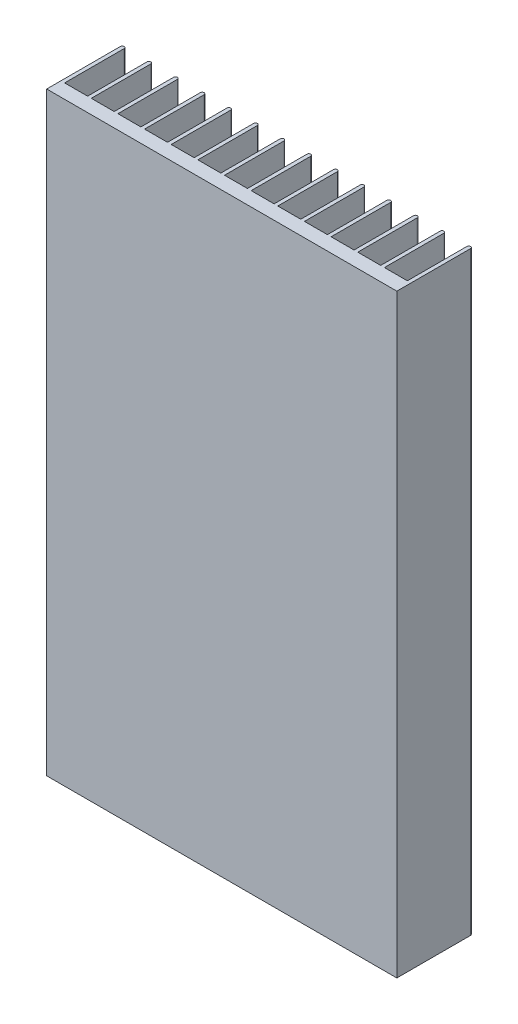
SolidWorks part; units mm, degrees
material "6063-T5"
ref_plane "X-Y Datum" through (0, 0, 0) normal (0, 0, 1) x (1, 0, 0)
ref_plane "X-Z Datum" through (0, 0, 0) normal (0, 1, 0) x (1, 0, 0)
ref_plane "Y-Z Datum" through (0, 0, 0) normal (1, 0, 0) x (0, 0, -1)
sketch "Sketch1" plane through (0, 0, 0) normal (0, 1, 0) x (1, 0, 0)
  line L0 (0, 0) -> (149.5044, 0)
  line L1 (0, 0) -> (0, 31.4706)
  line L2 (1.5748, 6.0706) -> (11.3792, 6.0706)
  line L3 (1.5748, 31.4706) -> (1.5748, 6.0706)
  line L4 (12.954, 31.4706) -> (12.954, 6.0706)
  line L5 (11.3792, 6.0706) -> (11.3792, 31.4706)
  line L6 (24.3332, 31.4706) -> (24.3332, 6.0706)
  line L7 (22.7584, 6.0706) -> (22.7584, 31.4706)
  line L8 (35.7124, 31.4706) -> (35.7124, 6.0706)
  line L9 (34.1376, 6.0706) -> (34.1376, 31.4706)
  line L10 (47.0916, 31.4706) -> (47.0916, 6.0706)
  line L11 (45.5168, 6.0706) -> (45.5168, 31.4706)
  line L12 (58.4708, 31.4706) -> (58.4708, 6.0706)
  line L13 (56.896, 6.0706) -> (56.896, 31.4706)
  line L14 (69.85, 31.4706) -> (69.85, 6.0706)
  line L15 (68.2752, 6.0706) -> (68.2752, 31.4706)
  line L16 (81.2292, 31.4706) -> (81.2292, 6.0706)
  line L17 (79.6544, 6.0706) -> (79.6544, 31.4706)
  line L18 (92.6084, 31.4706) -> (92.6084, 6.0706)
  line L19 (91.0336, 6.0706) -> (91.0336, 31.4706)
  line L20 (103.9876, 31.4706) -> (103.9876, 6.0706)
  line L21 (102.4128, 6.0706) -> (102.4128, 31.4706)
  line L22 (115.3668, 31.4706) -> (115.3668, 6.0706)
  line L23 (113.792, 6.0706) -> (113.792, 31.4706)
  line L24 (126.746, 31.4706) -> (126.746, 6.0706)
  line L25 (125.1712, 6.0706) -> (125.1712, 31.4706)
  line L26 (138.1252, 31.4706) -> (138.1252, 6.0706)
  line L27 (136.5504, 6.0706) -> (136.5504, 31.4706)
  line L28 (149.5044, 31.4706) -> (149.5044, 6.0706)
  line L29 (147.9296, 6.0706) -> (147.9296, 31.4706)
  line L30 (12.954, 6.0706) -> (22.7584, 6.0706)
  line L31 (149.5044, 0) -> (149.5044, 6.0706)
  line L32 (24.3332, 6.0706) -> (34.1376, 6.0706)
  line L33 (35.7124, 6.0706) -> (45.5168, 6.0706)
  line L34 (47.0916, 6.0706) -> (56.896, 6.0706)
  line L35 (69.85, 6.0706) -> (79.6544, 6.0706)
  line L36 (81.2292, 6.0706) -> (91.0336, 6.0706)
  line L37 (92.6084, 6.0706) -> (102.4128, 6.0706)
  line L38 (103.9876, 6.0706) -> (113.792, 6.0706)
  line L39 (115.3668, 6.0706) -> (125.1712, 6.0706)
  line L40 (126.746, 6.0706) -> (136.5504, 6.0706)
  line L41 (138.1252, 6.0706) -> (147.9296, 6.0706)
  line L42 (58.4708, 6.0706) -> (68.2752, 6.0706)
  arc A0 (1.5748, 31.4706) -> (0, 31.4706) centre (0.7874, 31.4706) ccw
  arc A1 (12.954, 31.4706) -> (11.3792, 31.4706) centre (12.1666, 31.4706) ccw
  arc A2 (24.3332, 31.4706) -> (22.7584, 31.4706) centre (23.5458, 31.4706) ccw
  arc A3 (35.7124, 31.4706) -> (34.1376, 31.4706) centre (34.925, 31.4706) ccw
  arc A4 (47.0916, 31.4706) -> (45.5168, 31.4706) centre (46.3042, 31.4706) ccw
  arc A5 (58.4708, 31.4706) -> (56.896, 31.4706) centre (57.6834, 31.4706) ccw
  arc A6 (69.85, 31.4706) -> (68.2752, 31.4706) centre (69.0626, 31.4706) ccw
  arc A7 (81.2292, 31.4706) -> (79.6544, 31.4706) centre (80.4418, 31.4706) ccw
  arc A8 (92.6084, 31.4706) -> (91.0336, 31.4706) centre (91.821, 31.4706) ccw
  arc A9 (103.9876, 31.4706) -> (102.4128, 31.4706) centre (103.2002, 31.4706) ccw
  arc A10 (115.3668, 31.4706) -> (113.792, 31.4706) centre (114.5794, 31.4706) ccw
  arc A11 (126.746, 31.4706) -> (125.1712, 31.4706) centre (125.9586, 31.4706) ccw
  arc A12 (138.1252, 31.4706) -> (136.5504, 31.4706) centre (137.3378, 31.4706) ccw
  arc A13 (149.5044, 31.4706) -> (147.9296, 31.4706) centre (148.717, 31.4706) ccw
  dimension "D1" = 14
extrude "Boss-Extrude1" add sketch "Sketch1" along normal blind 254
